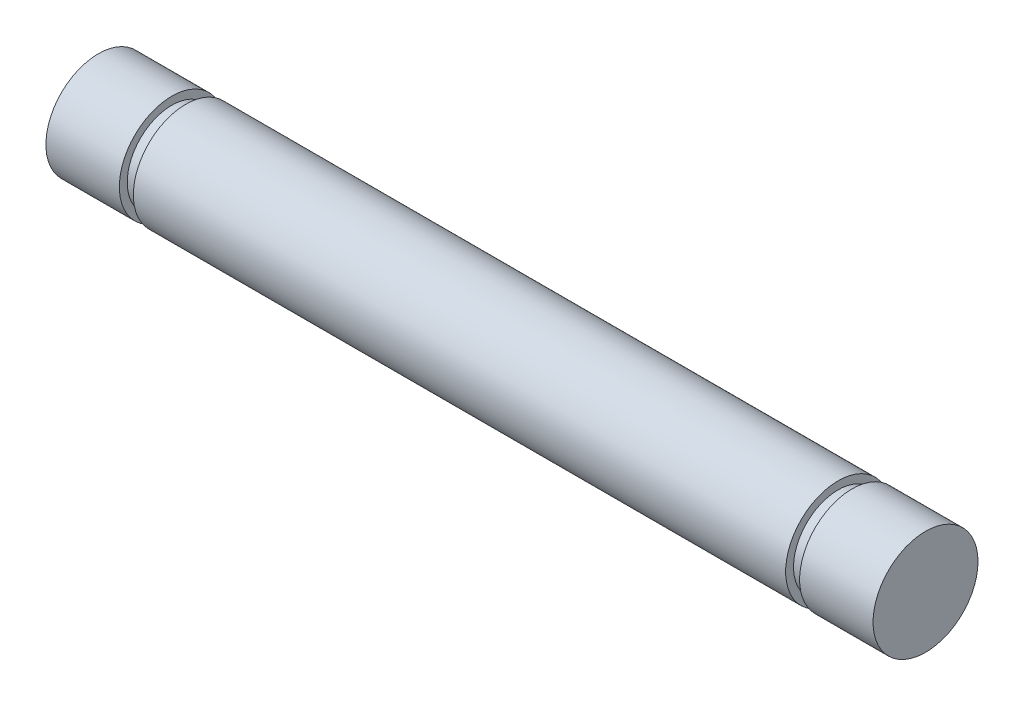
SolidWorks part; units mm, degrees
ref_plane "Alzado" through (0, 0, 0) normal (1, 0, 0) x (0, 1, 0)
ref_plane "Planta" through (0, 0, 0) normal (0, 0, 1) x (0, 1, 0)
ref_plane "Vista lateral" through (0, 0, 0) normal (0, 1, 0) x (-1, 0, 0)
sketch "Croquis1" plane through (0, 0, 0) normal (0, 1, 0) x (-1, 0, 0)
  line L1 (-18.65, 3) -> (18.65, 3)
  line L6 (23.65, 3) -> (23.65, 0)
  line L7 (-23.65, 0) -> (23.65, 0) construction
  line L22 (-23.65, 0) -> (23.65, 0)
  line L23 (18.65, 3) -> (18.65, 2.55)
  line L24 (18.65, 2.55) -> (19.45, 2.55)
  line L25 (19.45, 2.55) -> (19.45, 3)
  line L26 (19.45, 3) -> (23.65, 3)
  line L27 (0, 0) -> (0, 3) construction
  line L28 (-19.45, 3) -> (-23.65, 3)
  line L29 (-19.45, 2.55) -> (-19.45, 3)
  line L30 (-18.65, 2.55) -> (-19.45, 2.55)
  line L31 (-18.65, 3) -> (-18.65, 2.55)
  line L32 (-23.65, 3) -> (-23.65, 0)
  dimension "D1" = 5
  dimension "D2" = 6
  dimension "D3" = 37.3
  dimension "D5" = 0.8
  dimension "D7" = 0.45
revolve "Revolución1" add sketch "Croquis1" angle 360 about L7
equation "\"ancho_circlip\"=0.8"
equation "\"ranura_circlip\"=0.45"
